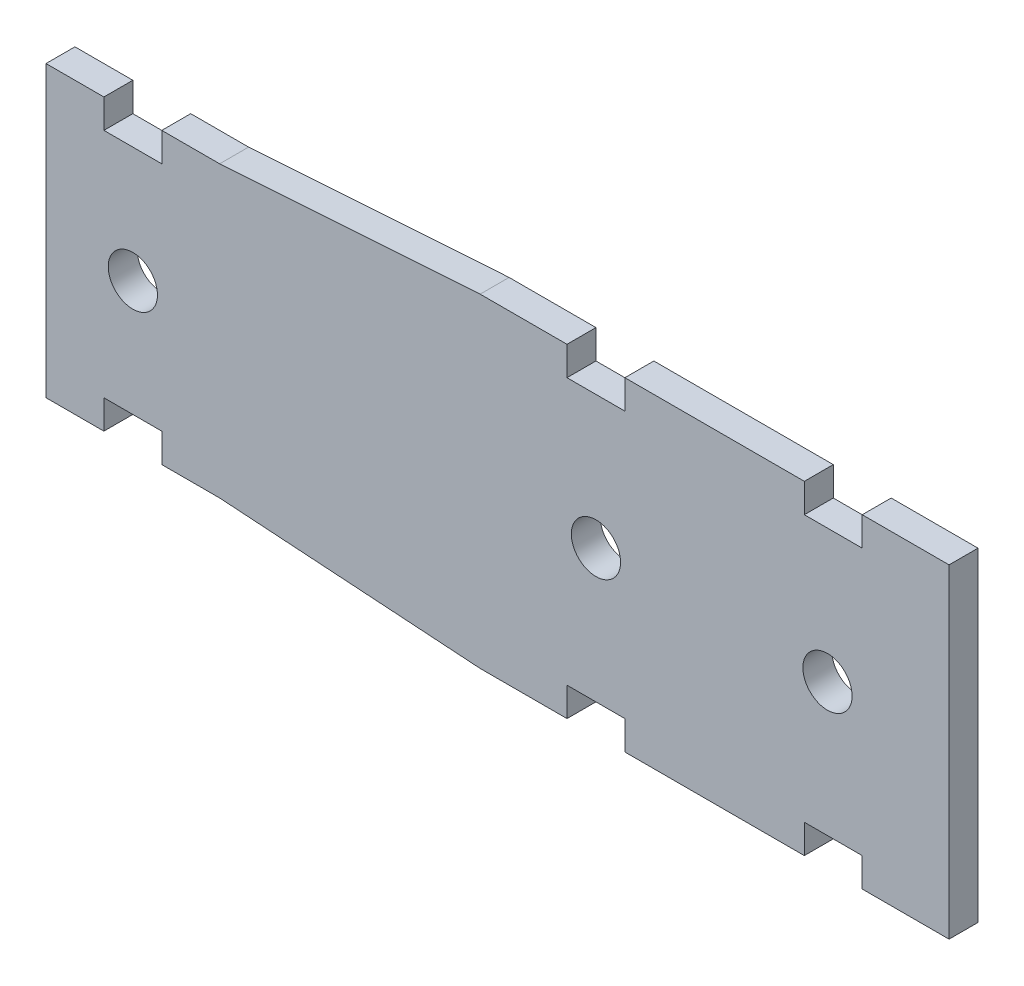
SolidWorks part; units mm, degrees
ref_plane "Front Plane" through (0, 0, 0) normal (1, 0, 0) x (0, 1, 0)
ref_plane "Top Plane" through (0, 0, 0) normal (0, 0, 1) x (0, 1, 0)
ref_plane "Right Plane" through (0, 0, 0) normal (0, 1, 0) x (-1, 0, 0)
sketch "Sketch1" plane through (0, 0, 0) normal (0, 0, 1) x (0, 1, 0)
  line L0 (0, 0) -> (0, 36284.5455) construction
  line L1 (-25, 50) -> (25, 50)
  line L2 (25, 50) -> (25, 40)
  line L3 (25, 40) -> (20, 40)
  line L4 (20, 40) -> (20, 30)
  line L5 (20, 30) -> (25, 30)
  line L6 (25, 30) -> (25, 20)
  line L7 (20, 35) -> (0, 35) construction
  line L8 (0, 35) -> (0, -25) construction
  line L9 (0, -25) -> (28, -25) construction
  line L10 (25, 20) -> (28, -25)
  line L11 (28, -25) -> (28, -40)
  line L12 (28, -25) -> (28, -40)
  line L13 (28, -50) -> (28, -86)
  line L14 (28, -106) -> (-28, -106)
  line L15 (28, -50) -> (28, -45) construction
  line L16 (28, -40) -> (23, -40)
  line L17 (28, -50) -> (23, -50)
  line L18 (23, -50) -> (23, -40)
  line L19 (28, -50) -> (28, -106)
  line L20 (28, -40) -> (28, -45) construction
  line L21 (28, -45) -> (28, -50) construction
  line L22 (28, -40) -> (28, -45) construction
  line L23 (28, -45) -> (28, -40) construction
  line L24 (28, -45) -> (28, -50) construction
  line L25 (28, -91) -> (28, -81)
  line L26 (28, -81) -> (23, -81)
  line L27 (23, -81) -> (23, -91)
  line L28 (23, -91) -> (28, -91)
  line L29 (28, -40) -> (28, -50)
  line L30 (-28, -50) -> (-28, -106)
  line L31 (-23, -91) -> (-28, -91)
  line L32 (-23, -81) -> (-23, -91)
  line L33 (-28, -81) -> (-23, -81)
  line L34 (-28, -50) -> (-28, -86)
  line L35 (-28, -50) -> (-23, -50)
  line L36 (-23, -50) -> (-23, -40)
  line L37 (-28, -40) -> (-23, -40)
  line L38 (-28, -25) -> (-28, -40)
  line L39 (-25, 20) -> (-28, -25)
  line L40 (-25, 30) -> (-25, 20)
  line L41 (-20, 30) -> (-25, 30)
  line L42 (-20, 40) -> (-20, 30)
  line L43 (-25, 40) -> (-20, 40)
  line L44 (-25, 50) -> (-25, 40)
  point P21 (28, -45)
  point P26 (28, -86)
  point P29 (0, -106)
  point P45 (0, 50)
  dimension "D1" = 25
  dimension "D2" = 10
  dimension "D3" = 10
  dimension "D4" = 5
  dimension "D5" = 50
  dimension "D6" = 28
  dimension "D7" = 60
  dimension "D8" = 20
  dimension "D9" = 41
  dimension "D10" = 20
  dimension "D11" = 10
  dimension "D12" = 5
  dimension "D13" = 10
  dimension "D14" = 5
extrude "Boss-Extrude1" add sketch "Sketch1" along normal mid plane 5 contours L1 L44 L43 L42 L41 L40 L39 L38 L37 L36 L35 L30 L33 L32 L31 L14 L19 L28 L27 L26 L13 L17 L18 L16 L11 L10 L6 L5 L4 L3 L2
sketch "Sketch2" plane through (0, 0, 2.5) normal (0, 0, 1) x (1, 0, 0)
  line L0 (-50, 0) -> (106, 0) construction
  line L1 (-50, -25) -> (-50, 25) construction
  line L2 (106, 28) -> (106, -28) construction
  line L3 (-50, 0) -> (-35, 0)
  line L4 (-35, 0) -> (45, 0)
  line L5 (45, 0) -> (85, 0)
  circle A0 centre (-35, 0) radius 4.25
  circle A1 centre (45, 0) radius 4.25
  circle A2 centre (85, 0) radius 4.25
  dimension "D4" = 8.5
  dimension "D1" = 15
  dimension "D2" = 80
  dimension "D3" = 40
extrude "Cut-Extrude1" cut sketch "Sketch2" against normal up to next contours A0 | A1 | A2
